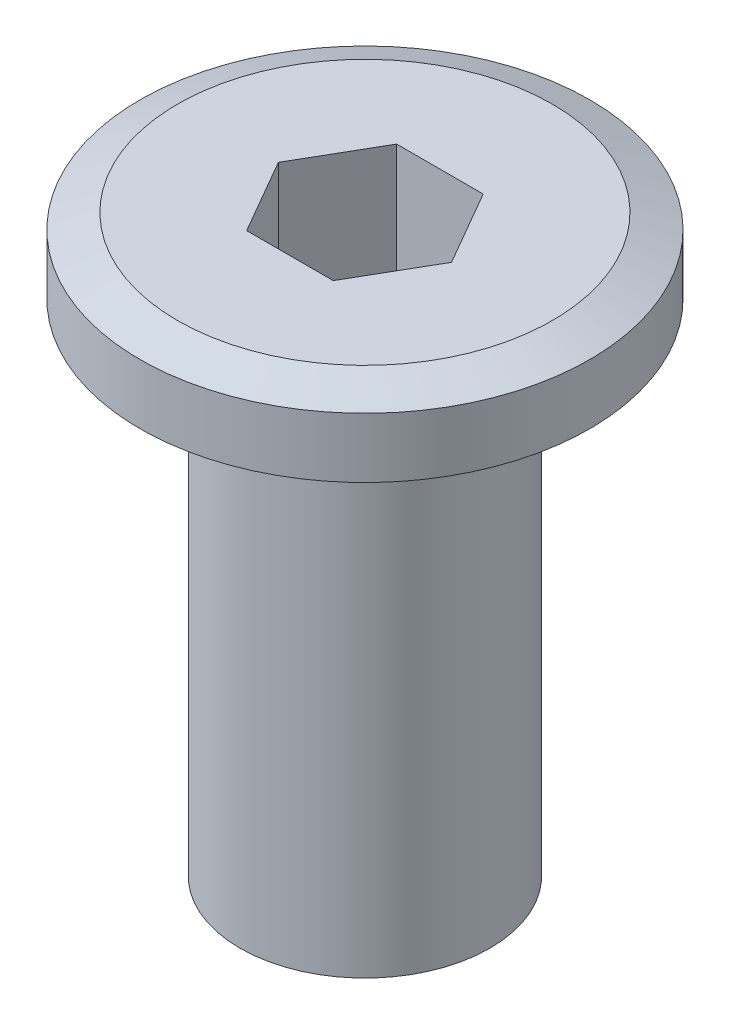
SolidWorks part; units mm, degrees
ref_plane "Front Plane" through (0, 0, 0) normal (0, 0, 1) x (1, 0, 0)
ref_plane "Top Plane" through (0, 0, 0) normal (0, 1, 0) x (1, 0, 0)
ref_plane "Right Plane" through (0, 0, 0) normal (1, 0, 0) x (0, 0, -1)
sketch "Sketch1" plane through (0, 0, 0) normal (0, 0, 1) x (1, 0, 0)
  line L0 (0, 0) -> (0, 1.5)
  line L1 (-2.5, 0) -> (2.5, 0)
  line L5 (-4.5, 0) -> (4.5, 0)
  line L6 (-4.5, 0) -> (-4.5, 1.5)
  line L7 (-4.5, 1.5) -> (4.5, 1.5)
  line L8 (4.5, 0) -> (4.5, 1.5)
  line L9 (-4.5, 1.2) -> (-3.75, 1.5)
  point P1 (0, 0)
  point P8 (0, 1.5)
  dimension "D1" = 3.75
  dimension "D3" = 9
  dimension "D4" = 1.5
  dimension "D6" = 1.2
revolve "Revolve1" add sketch "Sketch1" angle 360 about L0
sketch "Sketch2" plane through (0, 1.5, 0) normal (0, 1, 0) x (1, 0, 0)
  line L1 (1.7321, 0) -> (0.866, 1.5)
  line L2 (0.866, 1.5) -> (-0.866, 1.5)
  line L3 (-0.866, 1.5) -> (-1.7321, 0)
  line L4 (-1.7321, 0) -> (-0.866, -1.5)
  line L5 (-0.866, -1.5) -> (0.866, -1.5)
  line L6 (0.866, -1.5) -> (1.7321, 0)
  circle A0 centre (0, 0) radius 1.5 construction
  dimension "D1" = 3
sketch "Sketch3" plane through (0, 0, 0) normal (0, -1, 0) x (1, 0, 0)
  circle A0 centre (0, 0) radius 2.5
  dimension "D1" = 5
extrude "Boss-Extrude1" add sketch "Sketch3" along normal blind 10
extrude "Cut-Extrude2" cut sketch "Sketch2" against normal blind 3 contours L1 L2 L3 L4 L5 L6
